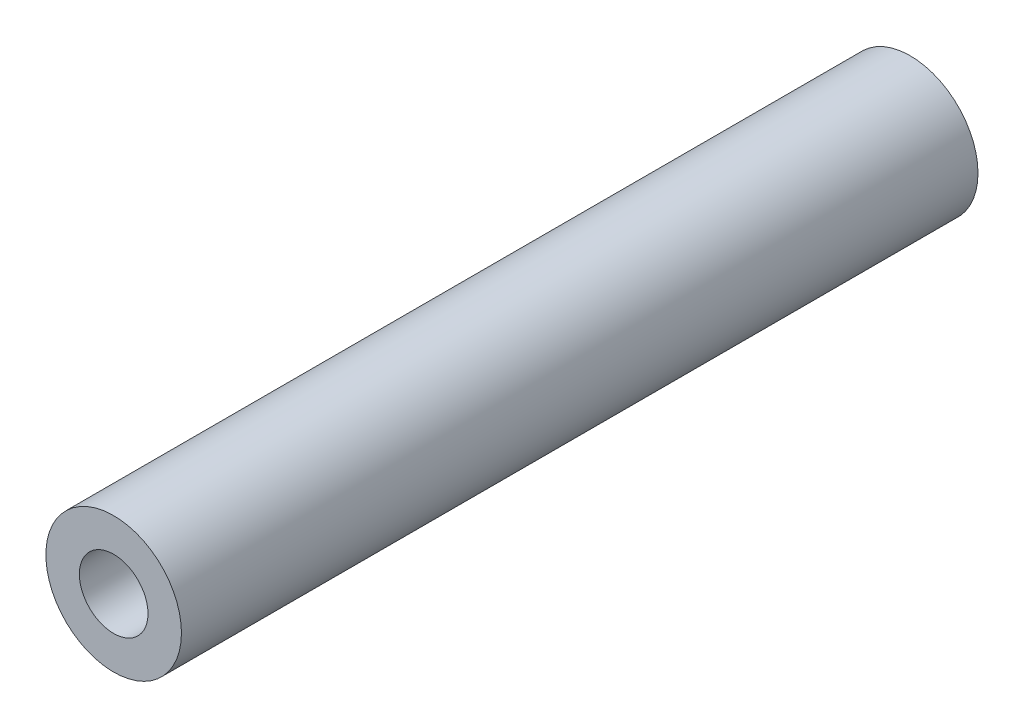
SolidWorks part; units mm, degrees
ref_plane "Front Plane" through (0, 0, 0) normal (0, 0, 1) x (1, 0, 0)
ref_plane "Top Plane" through (0, 0, 0) normal (0, 1, 0) x (1, 0, 0)
ref_plane "Right Plane" through (0, 0, 0) normal (1, 0, 0) x (0, 0, -1)
sketch "S01 - Solid post blank - 16 mm" plane through (0, 0, 0) normal (0, 0, 1) x (1, 0, 0)
  circle A0 centre (0, 0) radius 8
extrude "01 - Solid post blank - 16 mm" add sketch "S01 - Solid post blank - 16 mm" along normal blind 94
sketch "S02 - Rear M6 heat-set insert seat" plane through (0, 0, 0) normal (0, 0, 1) x (1, 0, 0)
  circle A0 centre (0, 0) radius 4.05
extrude "02 - Rear M6 heat-set insert seat" cut sketch "S02 - Rear M6 heat-set insert seat" along normal blind 14.35 from offset 0.1 offset against normal yes
sketch "S03 - Front M6 heat-set insert seat" plane through (0, 0, 0) normal (0, 0, 1) x (1, 0, 0)
  circle A0 centre (0, 0) radius 4.05
extrude "03 - Front M6 heat-set insert seat" cut sketch "S03 - Front M6 heat-set insert seat" along normal blind 14.35 from offset 79.75
